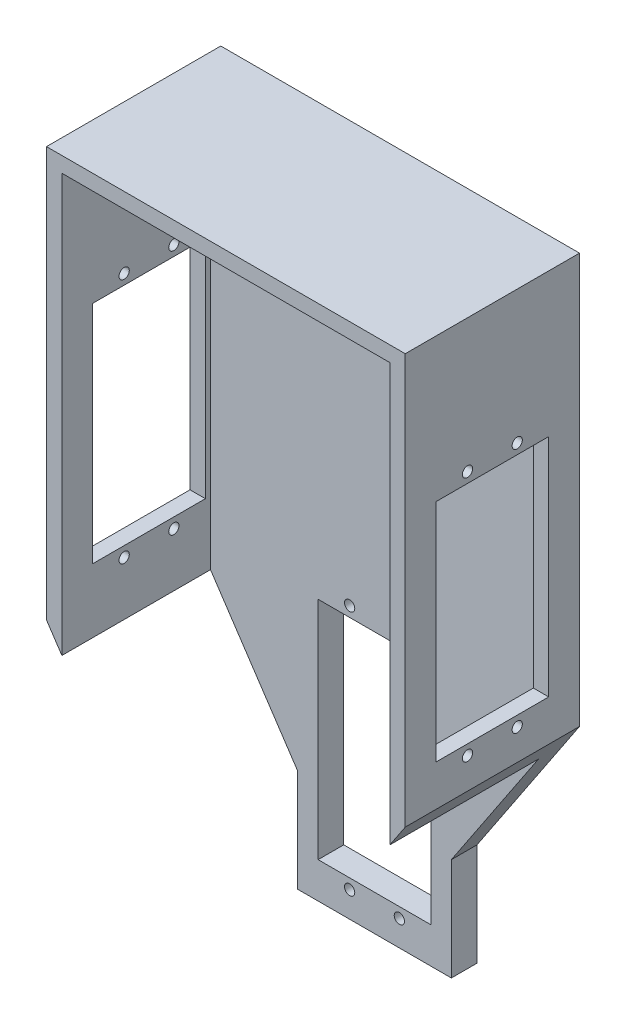
SolidWorks part; units mm, degrees
material "Polylactic Acid"
ref_plane "Front Plane" through (0, 0, 0) normal (0, 0, 1) x (1, 0, 0)
ref_plane "Top Plane" through (0, 0, 0) normal (0, 1, 0) x (1, 0, 0)
ref_plane "Right Plane" through (0, 0, 0) normal (1, 0, 0) x (0, 0, -1)
sketch "Sketch1" plane through (0, 0, 0) normal (0, 0, 1) x (1, 0, 0)
  line L0 (-4.85, -24) -> (4.85, -24) construction
  line L1 (11, -22) -> (-11, -22)
  line L2 (11, -22) -> (11, 22)
  line L3 (11, 22) -> (-11, 22)
  line L4 (-11, -22) -> (-11, 22)
  line L5 (11, -22) -> (-11, 22) construction
  line L6 (11, 22) -> (-11, -22) construction
  line L7 (-4.85, -24) -> (-4.85, 24) construction
  line L8 (-15, -29) -> (15, -29)
  line L9 (15, -29) -> (15, -9)
  line L10 (15, -9) -> (35, 21)
  line L11 (35, 21) -> (35, 101)
  line L12 (35, 101) -> (-35, 101)
  line L13 (-35, 101) -> (-35, 21)
  line L14 (-35, 21) -> (-15, -9)
  line L15 (-15, -9) -> (-15, -29)
  circle A0 centre (-4.85, -24) radius 1
  circle A1 centre (4.85, -24) radius 1
  circle A2 centre (4.85, 24) radius 1
  circle A3 centre (-4.85, 24) radius 1
  point P0 (0, 0)
  point P8 (0, -24)
  point P10 (0, -22)
  point P19 (-4.85, 0)
  point P20 (-11, 0)
  point P32 (0, -29)
  dimension "D5" = 2
  dimension "D1" = 9.7
  dimension "D2" = 48
  dimension "D6" = 44
  dimension "D7" = 22
  dimension "D8" = 30
  dimension "D9" = 20
  dimension "D10" = 5
  dimension "D11" = 30
  dimension "D12" = 20
  dimension "D13" = 80
  dimension "D3" = 2
  dimension "D4" = 2
extrude "Boss-Extrude1" add sketch "Sketch1" along normal mid plane 5
sketch "Sketch2" plane through (0, 0, -2.5) normal (0, 0, 1) x (1, 0, 0)
  line L0 (15, -9) -> (35, 21) construction
  line L5 (-35, 101) -> (-35, 21) construction
  line L7 (-35, 101) -> (-35, 21)
  line L8 (-35, 21) -> (-32, 16.5)
  line L9 (-32, 98) -> (-32, 16.5)
  line L10 (32, 16.5) -> (35, 21)
  line L11 (32, 16.5) -> (32, 98)
  line L13 (35, 21) -> (35, 101)
  line L14 (35, 21) -> (35, 101) construction
  line L15 (-35, 101) -> (35, 101)
  line L16 (-35, 21) -> (-15, -9) construction
  line L17 (32, 98) -> (-32, 98)
  point P4 (35, 86)
  point P9 (-35, 86)
  dimension "D1" = 3
  dimension "D2" = 3
extrude "Boss-Extrude2" add sketch "Sketch2" along normal blind 34
sketch "Sketch3" plane through (-35, 0, 0) normal (-1, 0, 0) x (0, 0, 1)
  line L0 (9.65, 27) -> (19.35, 27) construction
  line L1 (3.5, 29) -> (25.5, 29)
  line L2 (3.5, 29) -> (3.5, 73)
  line L3 (3.5, 73) -> (25.5, 73)
  line L4 (25.5, 29) -> (25.5, 73)
  line L5 (3.5, 29) -> (25.5, 73) construction
  line L6 (3.5, 73) -> (25.5, 29) construction
  line L7 (9.65, 27) -> (9.65, 75) construction
  line L8 (31.5, 21) -> (-2.5, 21) construction
  line L10 (31.5, 21) -> (-2.5, 21) construction
  circle A0 centre (9.65, 27) radius 1
  circle A1 centre (19.35, 27) radius 1
  circle A2 centre (19.35, 75) radius 1
  circle A3 centre (9.65, 75) radius 1
  point P0 (14.5, 51)
  point P8 (9.65, 51)
  point P9 (14.5, 27)
  point P18 (0, 0)
  point P21 (14.5, 21)
  dimension "D7" = 2
  dimension "D1" = 9.7
  dimension "D2" = 48
  dimension "D3" = 44
  dimension "D4" = 22
  dimension "D8" = 30
  dimension "D5" = 2
  dimension "D6" = 2
extrude "Cut-Extrude1" cut sketch "Sketch3" against normal up to surface (70 mm away) up to face at (35, 61, 14.5)
